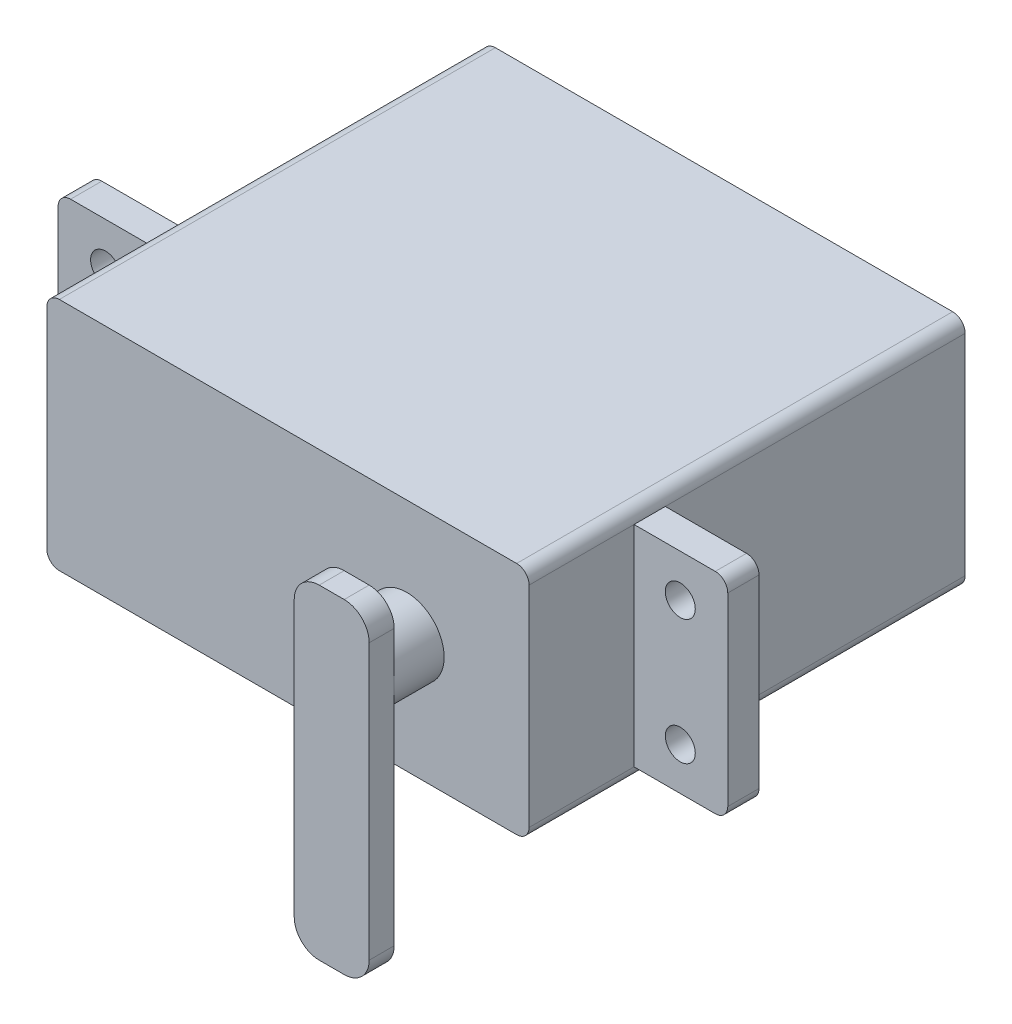
SolidWorks part; units mm, degrees
ref_plane "Front Plane" through (0, 0, 0) normal (0, 0, 1) x (1, 0, 0)
ref_plane "Top Plane" through (0, 0, 0) normal (0, 1, 0) x (1, 0, 0)
ref_plane "Right Plane" through (0, 0, 0) normal (1, 0, 0) x (0, 0, -1)
sketch "Sketch1" plane through (0, 0, 0) normal (0, 0, 1) x (1, 0, 0)
  line L0 (-18.3, -9.4) -> (18.3, -9.4)
  line L1 (19.3, -8.4) -> (19.3, 8.4)
  line L2 (18.3, 9.4) -> (-18.3, 9.4)
  line L3 (-19.3, 8.4) -> (-19.3, -8.4)
  arc A0 (18.3, -9.4) -> (19.3, -8.4) centre (18.3, -8.4) ccw
  arc A1 (19.3, 8.4) -> (18.3, 9.4) centre (18.3, 8.4) ccw
  arc A2 (-18.3, 9.4) -> (-19.3, 8.4) centre (-18.3, 8.4) ccw
  arc A3 (-19.3, -8.4) -> (-18.3, -9.4) centre (-18.3, -8.4) ccw
extrude "Boss-Extrude1" add sketch "Sketch1" along normal blind 34.9
ref_plane "Plane1" through (0, 0, 24) normal (0, 0, 1) x (1, 0, 0)
sketch "Sketch2" plane through (0, 0, 24) normal (0, 0, 1) x (1, 0, 0)
  line L0 (-25.8, -8.4) -> (25.8, -8.4)
  line L1 (26.8, -7.4) -> (26.8, 7.4)
  line L2 (25.8, 8.4) -> (-25.8, 8.4)
  line L3 (-26.8, 7.4) -> (-26.8, -7.4)
  arc A0 (25.8, -8.4) -> (26.8, -7.4) centre (25.8, -7.4) ccw
  arc A1 (26.8, 7.4) -> (25.8, 8.4) centre (25.8, 7.4) ccw
  arc A2 (-25.8, 8.4) -> (-26.8, 7.4) centre (-25.8, 7.4) ccw
  arc A3 (-26.8, -7.4) -> (-25.8, -8.4) centre (-25.8, -7.4) ccw
extrude "Boss-Extrude2" add sketch "Sketch2" along normal blind 2.5
ref_plane "Plane2" through (0, 0, 24) normal (0, 0, 1) x (1, 0, 0)
sketch "Sketch3" plane through (0, 0, 24) normal (0, 0, 1) x (1, 0, 0)
  circle A0 centre (23, 5) radius 1.2
  circle A1 centre (23, -5) radius 1.2
  circle A2 centre (-23, 5) radius 1.2
  circle A3 centre (-23, -5) radius 1.2
extrude "Cut-Extrude1" cut sketch "Sketch3" along normal blind 2.5
ref_plane "Plane3" through (0, 0, 34.9) normal (0, 0, 1) x (1, 0, 0)
sketch "Sketch4" plane through (0, 0, 34.9) normal (0, 0, 1) x (1, 0, 0)
  circle A0 centre (9.5, 0) radius 3
extrude "Boss-Extrude3" add sketch "Sketch4" along normal blind 4
ref_plane "Plane4" through (0, 0, 38.9) normal (0, 0, 1) x (1, 0, 0)
sketch "Sketch5" plane through (0, 0, 38.9) normal (0, 0, 1) x (1, 0, 0)
  line L0 (8.5, -20) -> (10.5, -20)
  line L1 (12.5, -18) -> (12.5, 4)
  line L2 (10.5, 6) -> (8.5, 6)
  line L3 (6.5, 4) -> (6.5, -18)
  arc A0 (10.5, -20) -> (12.5, -18) centre (10.5, -18) ccw
  arc A1 (12.5, 4) -> (10.5, 6) centre (10.5, 4) ccw
  arc A2 (8.5, 6) -> (6.5, 4) centre (8.5, 4) ccw
  arc A3 (6.5, -18) -> (8.5, -20) centre (8.5, -18) ccw
extrude "Boss-Extrude4" add sketch "Sketch5" along normal blind 2
